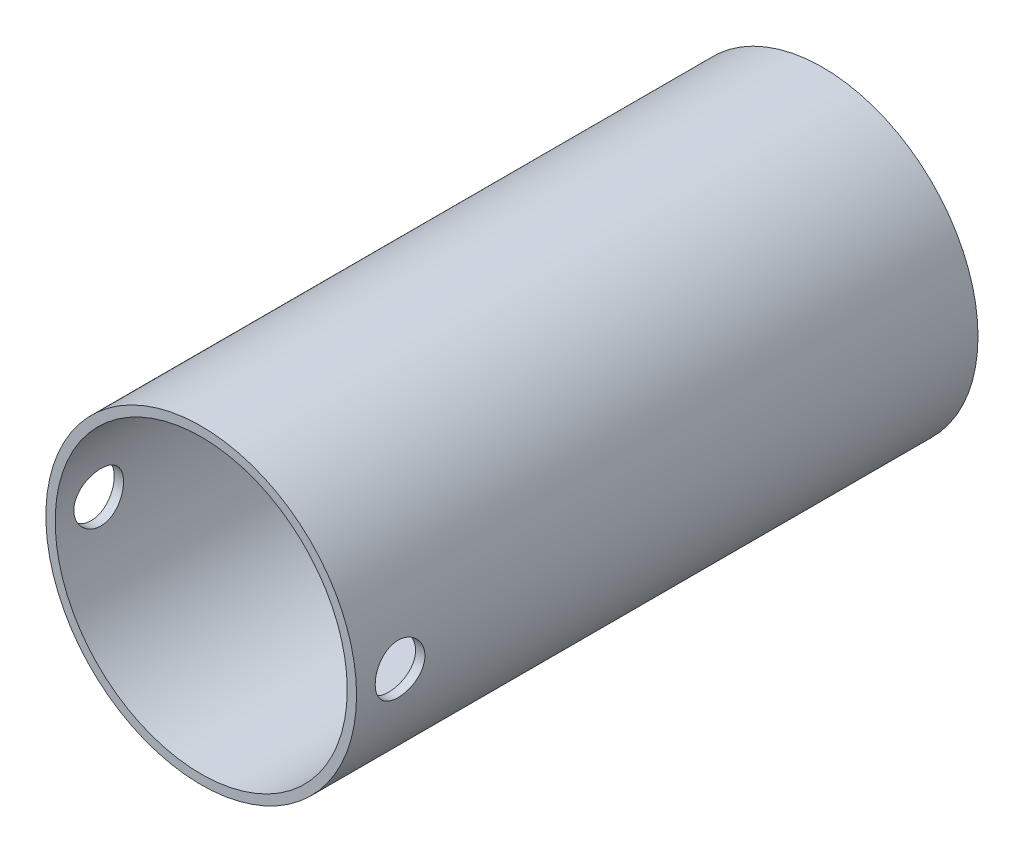
SolidWorks part; units mm, degrees
ref_plane "Alzado" through (0, 0, 0) normal (0, 0, 1) x (1, 0, 0)
ref_plane "Planta" through (0, 0, 0) normal (0, 1, 0) x (1, 0, 0)
ref_plane "Vista lateral" through (0, 0, 0) normal (1, 0, 0) x (0, 0, -1)
sketch "Croquis1" plane through (0, 0, 0) normal (0, 0, 1) x (1, 0, 0)
  circle A0 centre (0, 0) radius 23.5
  circle A1 centre (0, 0) radius 25
  dimension "D1" = 50
  dimension "D2" = 1.5
extrude "Saliente-Extruir1" add sketch "Croquis1" along normal blind 100
sketch "Croquis2" plane through (0, 0, 0) normal (1, 0, 0) x (0, 0, -1)
  line L1 (-100, 25) -> (-100, -25) construction
  circle A0 centre (-93, 0) radius 4
  dimension "D1" = 8
  dimension "D2" = 7
extrude "Cortar-Extruir1" cut sketch "Croquis2" against normal through all and the other way through all
